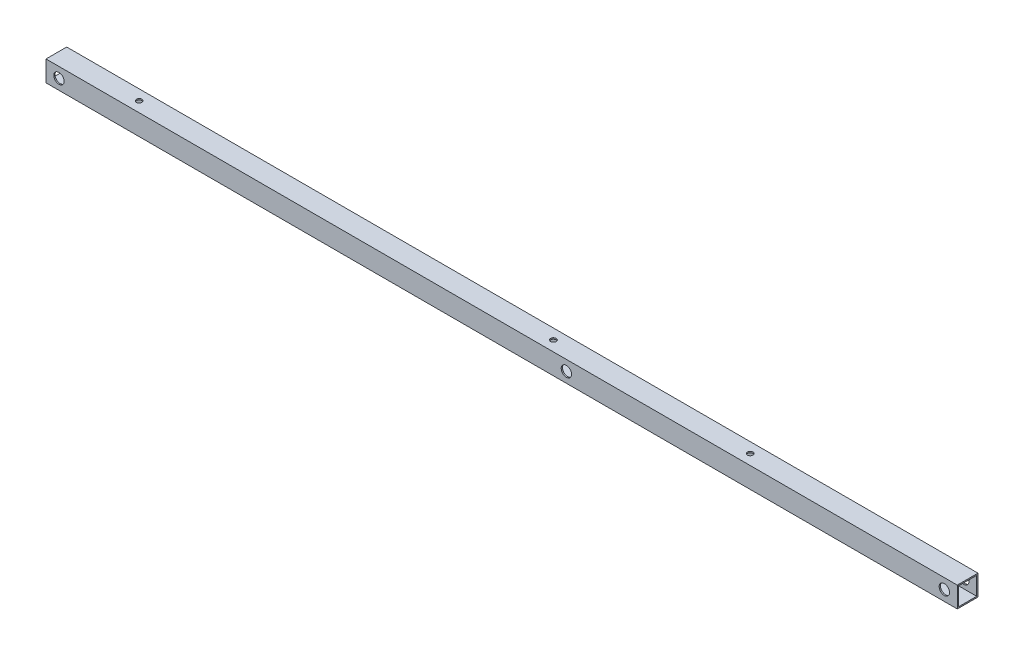
SolidWorks part; units mm, degrees
material "6063-O"
ref_plane "Front Plane" through (0, 0, 0) normal (0, 0, 1) x (1, 0, 0)
ref_plane "Top Plane" through (0, 0, 0) normal (0, 1, 0) x (1, 0, 0)
ref_plane "Right Plane" through (0, 0, 0) normal (1, 0, 0) x (0, 0, -1)
sketch "Sketch1" plane through (0, 0, 0) normal (1, 0, 0) x (0, 0, -1)
  line L1 (-12.7, -12.7) -> (12.7, -12.7)
  line L2 (-12.7, -12.7) -> (-12.7, 12.7)
  line L3 (-12.7, 12.7) -> (12.7, 12.7)
  line L4 (12.7, -12.7) -> (12.7, 12.7)
  line L5 (-12.7, -12.7) -> (12.7, 12.7) construction
  line L6 (-12.7, 12.7) -> (12.7, -12.7) construction
  point P0 (0, 0)
  dimension "D1" = 25.4
extrude "Extrude-Thin1" add sketch "Sketch1" along normal mid plane 1117.6 thin thin type one direction reverse wall 1.5875
hole_wizard "1/2 (0.5) Diameter Hole1" positions "Sketch2" profile "Sketch3" hole size "1/2" standard "ANSI Inch" end condition through all
sketch "Sketch2" plane through (0, 0, 12.7) normal (0, 0, 1) x (1, 0, 0)
  line L0 (13.97, 0) -> (-13.97, 0) construction
  line L1 (558.8, 12.7) -> (558.8, -12.7) construction
  line L2 (-558.8, 12.7) -> (-558.8, -12.7) construction
  point P0 (-542.925, 0)
  point P4 (542.925, 0)
  point P10 (79.375, 0)
  dimension "D1" = 15.875
  dimension "D2" = 15.875
  dimension "D3" = 463.55
sketch "Sketch3" plane through (-542.925, 0, 12.7) normal (1, 0, 0) x (0, -1, 0)
  line L0 (0, 0) -> (0, 25.4)
  line L1 (0, 25.4) -> (6.35, 25.4)
  line L2 (6.35, 25.4) -> (6.35, 0)
  line L5 (6.35, 0) -> (0, 0)
  line L11 (0, -6.35) -> (0, 107.95) construction
  dimension "Thru Hole Dia." = 12.7
  dimension "Thru Hole Depth" = 25.4
hole_wizard "1/4 Clearance Hole1" positions "Sketch6" profile "Sketch5" hole size "1/4" standard "ANSI Inch" end condition through all
sketch "Sketch6" plane through (0, 12.7, 0) normal (0, 1, 0) x (1, 0, 0)
  line L0 (-13.97, 0) -> (13.97, 0) construction
  line L1 (558.8, 12.7) -> (558.8, -12.7) construction
  line L2 (-558.8, 12.7) -> (-558.8, -12.7) construction
  line L3 (0, -13.97) -> (0, 13.97) construction
  point P0 (-457.2, 0)
  point P4 (50.8, 0)
  point P7 (292.1, 0)
  point P15 (0, 0)
  point P16 (27.8275, -3.3806)
  dimension "D1" = 266.7
  dimension "D2" = 101.6
  dimension "D3" = 50.8
sketch "Sketch5" plane through (-457.2, 12.7, 0) normal (1, 0, 0) x (0, 0, 1)
  line L0 (0, 0) -> (0, 25.4)
  line L1 (0, 25.4) -> (3.3782, 25.4)
  line L2 (3.3782, 25.4) -> (3.3782, 0)
  line L5 (3.3782, 0) -> (0, 0)
  line L11 (0, -6.35) -> (0, 107.95) construction
  dimension "Thru Hole Dia." = 6.7564
  dimension "Thru Hole Depth" = 25.4
